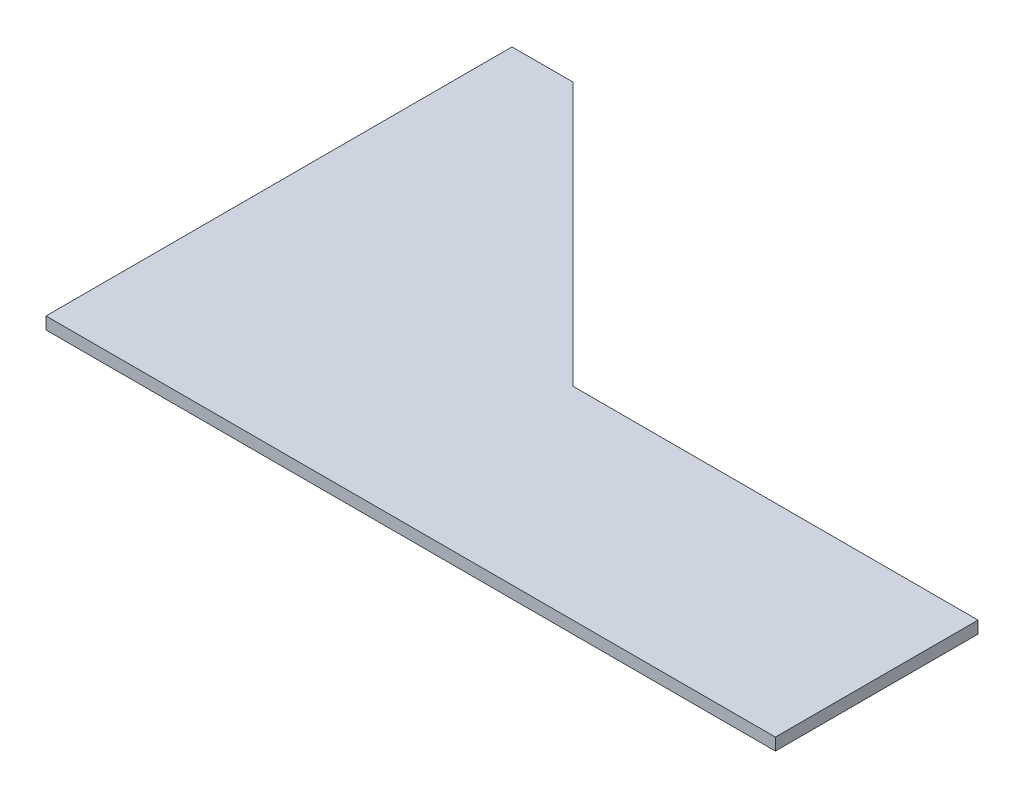
SolidWorks part; units mm, degrees
ref_plane "Plano frontal" through (0, 0, 0) normal (0, 0, 1) x (1, 0, 0)
ref_plane "Plano superior" through (0, 0, 0) normal (0, 1, 0) x (1, 0, 0)
ref_plane "Plano direito" through (0, 0, 0) normal (1, 0, 0) x (0, 0, -1)
sketch "Esboço1" plane through (0, 0, 0) normal (0, 1, 0) x (1, 0, 0)
  line L0 (0, 0) -> (0, 230)
  line L1 (0, 230) -> (30, 230)
  line L2 (0, 0) -> (360, 0)
  line L3 (360, 0) -> (360, 100)
  line L4 (360, 100) -> (160, 100)
  line L5 (30, 230) -> (160, 100)
  dimension "D1" = 230
  dimension "D2" = 360
  dimension "D3" = 100
  dimension "D4" = 200
  dimension "D5" = 30
  dimension "D6" = 183.8478
extrude "Ressalto-extrusão2" add sketch "Esboço1" along normal blind 6
